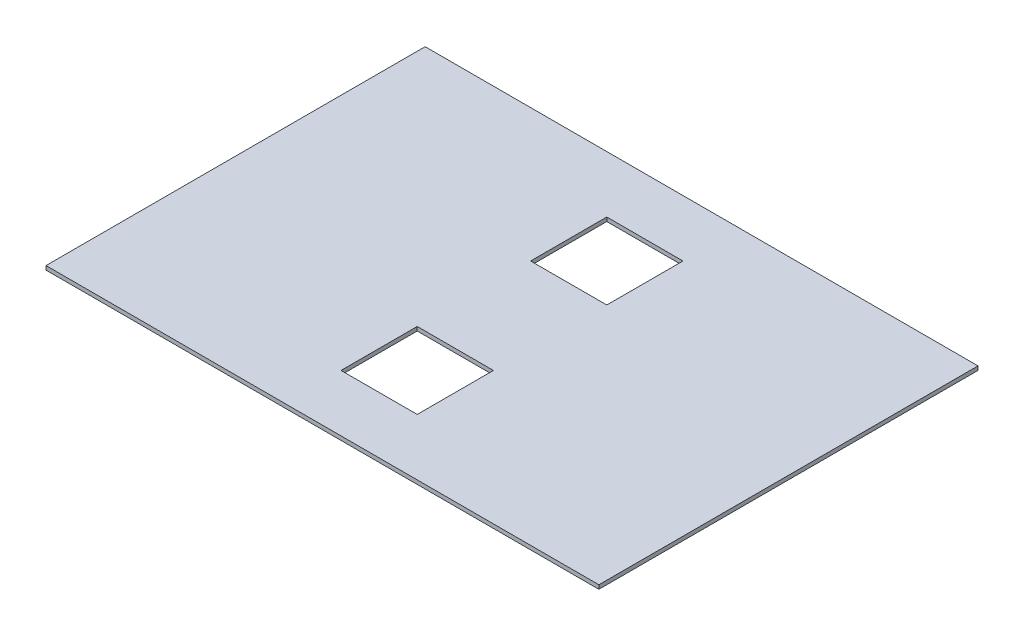
SolidWorks part; units mm, degrees
ref_plane "Front Plane" through (0, 0, 0) normal (0, 0, 1) x (1, 0, 0)
ref_plane "Top Plane" through (0, 0, 0) normal (0, 1, 0) x (1, 0, 0)
ref_plane "Right Plane" through (0, 0, 0) normal (1, 0, 0) x (0, 0, -1)
sketch "Sketch1" plane through (0, 0, 0) normal (0, 1, 0) x (1, 0, 0)
  line L1 (-444.5, -304.8) -> (444.5, -304.8)
  line L2 (-444.5, -304.8) -> (-444.5, 304.8)
  line L3 (-444.5, 304.8) -> (444.5, 304.8)
  line L4 (444.5, -304.8) -> (444.5, 304.8)
  line L5 (-444.5, -304.8) -> (444.5, 304.8) construction
  line L6 (-444.5, 304.8) -> (444.5, -304.8) construction
  point P0 (0, 0)
  dimension "D1" = 889
  dimension "D2" = 609.6
extrude "Boss-Extrude1" add sketch "Sketch1" along normal blind 6.35
sketch "Sketch2" plane through (0, 6.35, 0) normal (0, 1, 0) x (1, 0, 0)
  line L0 (0, 0) -> (0, 152.4) construction
  line L1 (-61.25, 213.65) -> (61.25, 213.65)
  line L2 (-61.25, 213.65) -> (-61.25, 91.15)
  line L3 (-61.25, 91.15) -> (61.25, 91.15)
  line L4 (61.25, 213.65) -> (61.25, 91.15)
  line L5 (-61.25, 213.65) -> (61.25, 91.15) construction
  line L6 (-61.25, 91.15) -> (61.25, 213.65) construction
  line L7 (0, 0) -> (444.5, 0) construction
  line L8 (444.5, -304.8) -> (444.5, 304.8) construction
  line L9 (-61.25, -91.15) -> (61.25, -91.15)
  line L10 (61.25, -213.65) -> (61.25, -91.15)
  line L11 (-61.25, -213.65) -> (61.25, -213.65)
  line L12 (-61.25, -213.65) -> (-61.25, -91.15)
  point P0 (0, 152.4)
  dimension "D1" = 122.5
  dimension "D2" = 122.5
  dimension "D3" = 152.4
extrude "Cut-Extrude1" cut sketch "Sketch2" against normal through all
